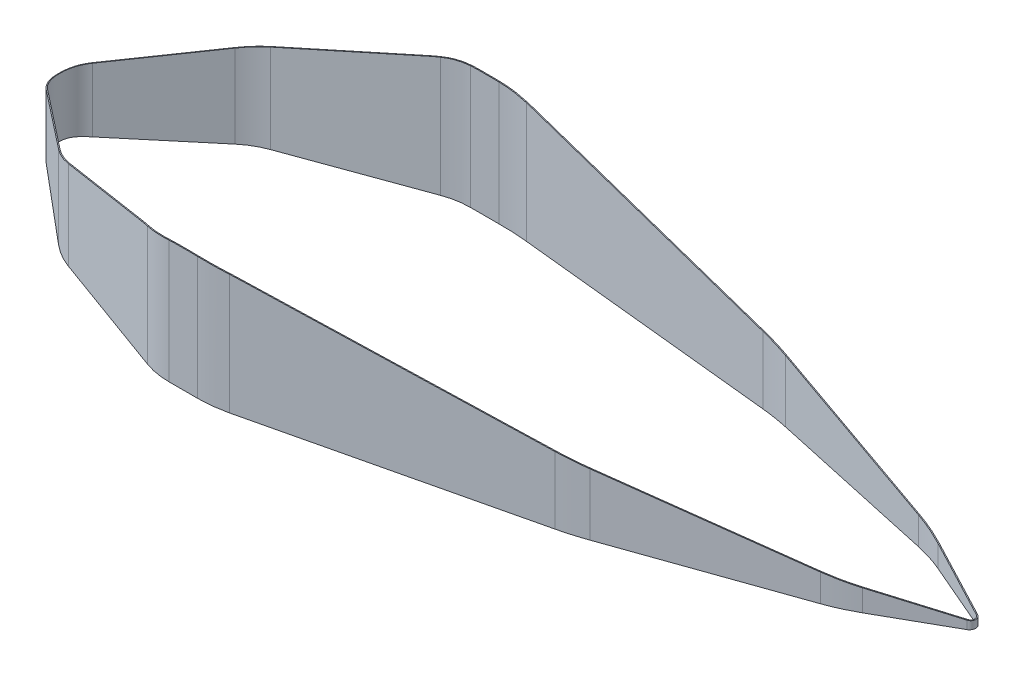
SolidWorks part; units mm, degrees
ref_plane "Front Plane" through (0, 0, 0) normal (0, 0, 1) x (1, 0, 0)
ref_plane "Top Plane" through (0, 0, 0) normal (0, 1, 0) x (1, 0, 0)
ref_plane "Right Plane" through (0, 0, 0) normal (1, 0, 0) x (0, 0, -1)
sketch "Sketch1" plane through (0, 0, 0) normal (0, 1, 0) x (1, 0, 0)
  line L0 (146.0698, 122.5671) -> (556.1483, 466.6637)
  line L1 (676.4552, 536.1229) -> (1335.1737, 775.877)
  line L2 (1471.9818, 800) -> (1622.7493, 800)
  line L3 (1779.1837, 787.6883) -> (3265.3831, 552.2976)
  line L4 (3418.9601, 519.6538) -> (4378.1346, 262.6437)
  line L5 (4541.9335, 203.0258) -> (4919.0165, 27.1892)
  line L6 (4919.0165, -27.1892) -> (4541.9335, -203.0258)
  line L7 (4378.1346, -262.6437) -> (3418.9601, -519.6538)
  line L8 (3265.3831, -552.2976) -> (1779.1837, -787.6883)
  line L9 (1622.7493, -800) -> (1471.9818, -800)
  line L10 (1335.1737, -775.877) -> (676.4552, -536.1229)
  line L11 (556.1483, -466.6637) -> (146.0698, -122.5671)
  arc A0 (146.0698, 122.5671) -> (146.0698, -122.5671) centre (248.9159, 0) ccw
  arc A1 (676.4552, -536.1229) -> (556.1483, -466.6637) centre (813.2633, -160.2459) cw
  arc A2 (1471.9818, -800) -> (1335.1737, -775.877) centre (1471.9818, -400) cw
  arc A3 (1335.1737, 775.877) -> (1471.9818, 800) centre (1471.9818, 400) cw
  arc A4 (556.1483, 466.6637) -> (676.4552, 536.1229) centre (813.2633, 160.2459) cw
  arc A5 (1779.1837, -787.6883) -> (1622.7493, -800) centre (1622.7493, 200) cw
  arc A6 (4541.9335, -203.0258) -> (4378.1346, -262.6437) centre (4119.3155, 703.2821) cw
  arc A7 (4378.1346, 262.6437) -> (4541.9335, 203.0258) centre (4119.3155, -703.2821) cw
  arc A8 (1622.7493, 800) -> (1779.1837, 787.6883) centre (1622.7493, -200) cw
  arc A9 (3418.9601, -519.6538) -> (3265.3831, -552.2976) centre (3030.7315, 929.2349) cw
  arc A10 (3265.3831, 552.2976) -> (3418.9601, 519.6538) centre (3030.7315, -929.2349) cw
  arc A11 (4919.0165, 27.1892) -> (4919.0165, -27.1892) centre (4906.3379, 0) cw
  point P15 (0, 0)
  point P18 (610.178, -512)
  point P21 (1401.451, -800)
  point P24 (1401.451, 800)
  point P27 (610.178, 512)
  point P30 (1701.451, -800)
  point P33 (4462.642, -240)
  point P36 (4462.642, 240)
  point P39 (1701.451, 800)
  point P42 (3343.027, -540)
  point P45 (3343.027, 540)
  point P48 (4977.324, 0)
  dimension "r0" = 160
  dimension "r1" = 400
  dimension "r3" = 1000
  dimension "r4" = 1500
  dimension "r6" = 30
  dimension "x1" = 610.178
  dimension "x2" = 1401.451
  dimension "x3" = 1701.451
  dimension "x4" = 3343.027
  dimension "x5" = 4462.642
  dimension "x6" = 4977.324
  dimension "x7" = 4462.642
  dimension "x8" = 3343.027
  dimension "x9" = 1701.451
  dimension "x10" = 1401.451
  dimension "x11" = 610.178
  dimension "y1" = 512
  dimension "y2" = 800
  dimension "y4" = 540
  dimension "y5" = 240
  dimension "y7" = 240
  dimension "y8" = 540
  dimension "y9" = 800
  dimension "y11" = 512
extrude "TopView_Extrude" add sketch "Sketch1" along normal blind 800
shell "Shell1" thickness 5
sketch "Sketch2" plane through (0, 0, 0) normal (0, 0, 1) x (1, 0, 0)
  line L0 (0, 300) -> (0, 332.8541)
  line L1 (113.6551, 478.3844) -> (1282.1337, 770.2016)
  line L2 (1524.433, 800) -> (1576.231, 800)
  line L3 (1825.6931, 784.3812) -> (4977.324, 388.181)
  line L4 (4977.324, 388.181) -> (4977.324, 355.91)
  line L5 (4977.324, 355.91) -> (1795.4573, 155.9089)
  line L6 (1607.2592, 150) -> (150, 150)
  arc A0 (0, 332.8541) -> (113.6551, 478.3844) centre (150, 332.8541) cw
  arc A1 (0, 300) -> (150, 150) centre (150, 300) ccw
  arc A2 (1282.1337, 770.2016) -> (1524.433, 800) centre (1524.433, -200) cw
  arc A3 (1576.231, 800) -> (1825.6931, 784.3812) centre (1576.231, -1200) cw
  arc A4 (1795.4573, 155.9089) -> (1607.2592, 150) centre (1607.2592, 3150) cw
  point P10 (0, 450)
  point P13 (0, 150)
  point P16 (1401.451, 800)
  point P19 (1701.451, 800)
  point P22 (1701.451, 150)
  dimension "r0" = 150
  dimension "r2" = 1000
  dimension "r3" = 2000
  dimension "r6" = 3000
  dimension "x2" = 1401.451
  dimension "x3" = 1701.451
  dimension "x4" = 4977.324
  dimension "x6" = 1701.451
  dimension "y0" = 150
  dimension "y1" = 450
  dimension "y2" = 800
  dimension "y4" = 388.181
  dimension "y5" = 355.91
extrude "SideProfile_Cut" cut sketch "Sketch2" against normal through all and the other way through all flip side to cut
